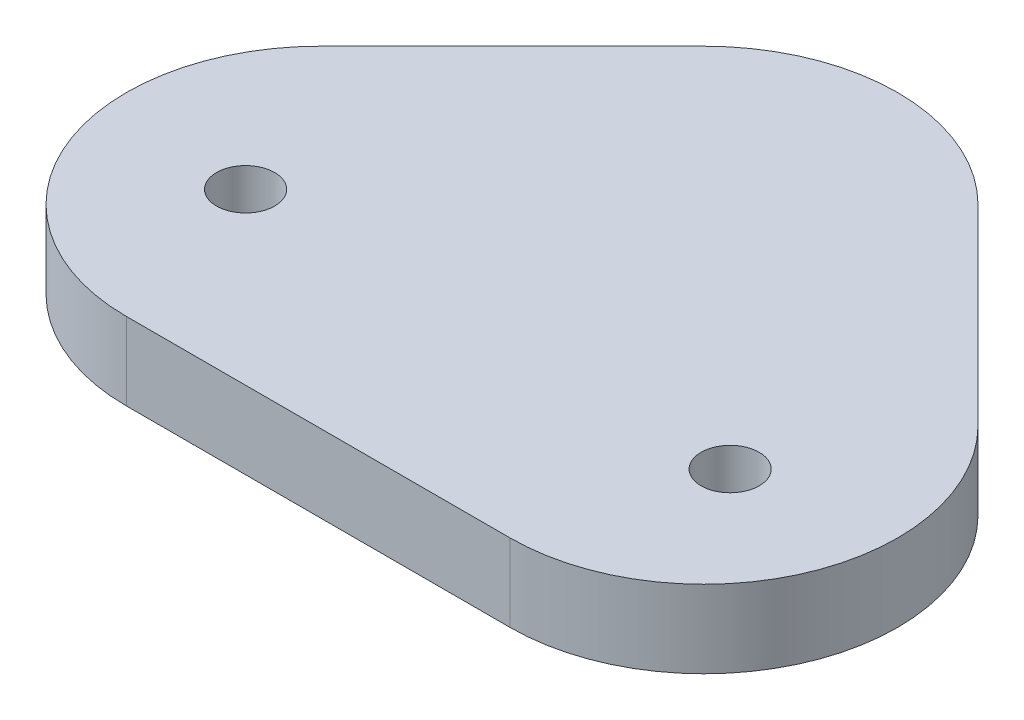
SolidWorks part; units mm, degrees
ref_plane "Ebene vorne" through (0, 0, 0) normal (0, 0, 1) x (1, 0, 0)
ref_plane "Ebene oben" through (0, 0, 0) normal (0, 1, 0) x (1, 0, 0)
ref_plane "Ebene rechts" through (0, 0, 0) normal (1, 0, 0) x (0, 0, -1)
sketch "Skizze2" plane through (0, 0, 0) normal (0, 1, 0) x (1, 0, 0)
  line L0 (26.9706, 26.9706) -> (17.0711, 17.0711)
  line L1 (24.1421, 0) -> (43.9411, 0)
  line L2 (-55, 0) -> (55, 0) construction
  line L3 (51.0122, 17.0711) -> (41.1127, 26.9706)
  line L4 (24.1421, 10) -> (43.9411, 10) construction
  arc A0 (26.9706, 26.9706) -> (41.1127, 26.9706) centre (34.0416, 19.8995) cw
  arc A1 (17.0711, 17.0711) -> (24.1421, 0) centre (24.1421, 10) ccw
  arc A2 (43.9411, 0) -> (51.0122, 17.0711) centre (43.9411, 10) ccw
  point P10 (0, 0)
  point P13 (68.0833, 0)
  dimension "D1" = 10
  dimension "D2" = 14
extrude "Aufsatz-Linear austragen1" add sketch "Skizze2" along normal blind 4
sketch "Skizze4" plane through (0, 0, 0) normal (0, 1, 0) x (1, 0, 0)
  line L0 (34.0416, 32.3709) -> (34.0416, -0.9038) construction
  circle A0 centre (21.5416, 8.755) radius 1.5
  circle A1 centre (46.5416, 8.755) radius 1.5
  dimension "D1" = 3
  dimension "D2" = 25
extrude "Schnitt-Linear austragen4" cut sketch "Skizze4" along normal up to surface (4 mm away) up to face at (34.0416, 4, -14.3812)
